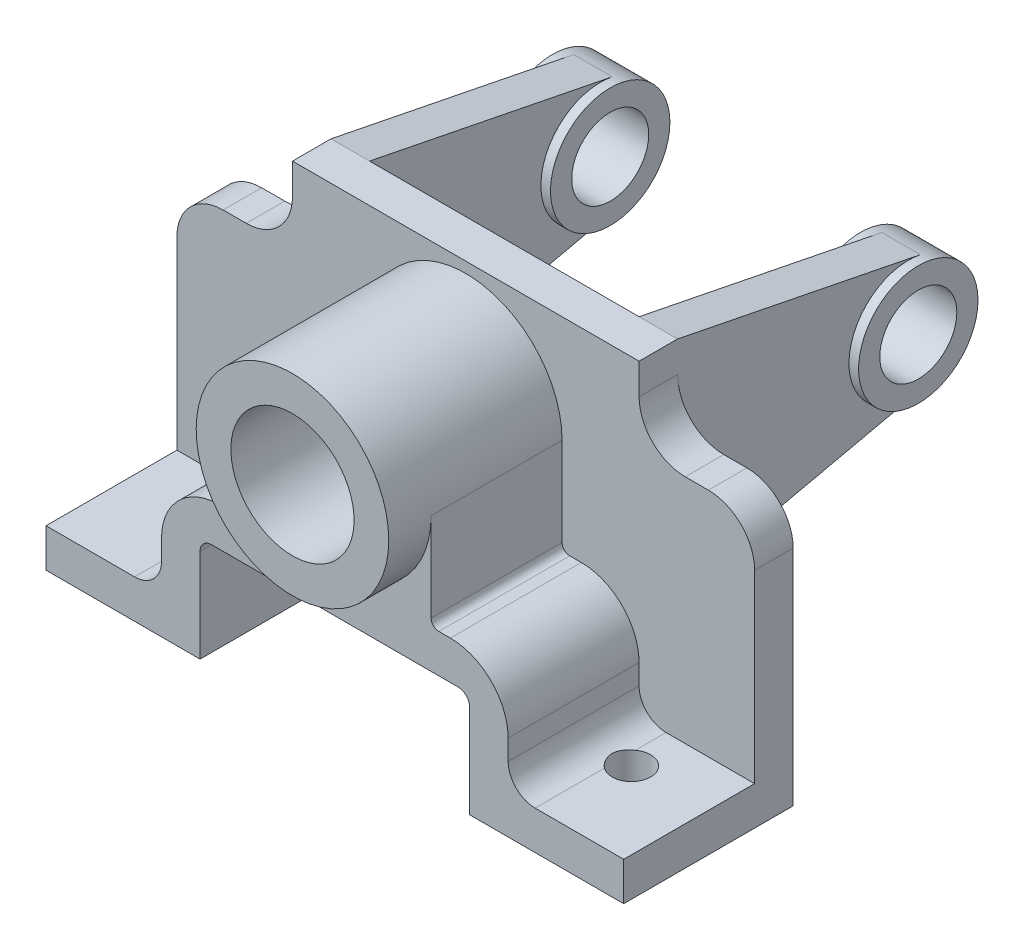
SolidWorks part; units mm, degrees
ref_plane "Front Plane" through (0, 0, 0) normal (0, 0, 1) x (1, 0, 0)
ref_plane "Top Plane" through (0, 0, 0) normal (0, 1, 0) x (1, 0, 0)
ref_plane "Right Plane" through (0, 0, 0) normal (1, 0, 0) x (0, 0, -1)
sketch "Sketch1" plane through (0, 0, 0) normal (0, 0, 1) x (1, 0, 0)
  line L0 (-32, 0) -> (32, 0)
  line L1 (35, -3) -> (35, -27.2359)
  line L2 (35, -27.2359) -> (75, -27.2359)
  line L3 (75, -27.2359) -> (75, 30.7641)
  line L4 (63, 42.7641) -> (57, 42.7641)
  line L5 (45, 54.7641) -> (45, 62.7641)
  line L6 (45, 62.7641) -> (-45, 62.7641)
  line L7 (-45, 62.7641) -> (-45, 54.7641)
  line L8 (-57, 42.7641) -> (-63, 42.7641)
  line L9 (-75, 30.7641) -> (-75, -27.2359)
  line L10 (-75, -27.2359) -> (-35, -27.2359)
  line L11 (-35, -27.2359) -> (-35, -3)
  line L12 (0, 62.7641) -> (0, 0) construction
  arc A0 (-63, 42.7641) -> (-75, 30.7641) centre (-63, 30.7641) ccw
  arc A1 (-45, 54.7641) -> (-57, 42.7641) centre (-57, 54.7641) cw
  arc A2 (75, 30.7641) -> (63, 42.7641) centre (63, 30.7641) ccw
  arc A3 (57, 42.7641) -> (45, 54.7641) centre (57, 54.7641) cw
  arc A4 (32, 0) -> (35, -3) centre (32, -3) cw
  arc A5 (-32, 0) -> (-35, -3) centre (-32, -3) ccw
  point P4 (0, 0)
  point P15 (0, 62.7641)
  point P22 (-45, 42.7641)
  point P25 (75, 42.7641)
  point P28 (45, 42.7641)
  point P31 (35, 0)
  dimension "D6" = 90
  dimension "D7" = 42.7641
  dimension "D8" = 12
  dimension "D9" = 3
  dimension "D1" = 70
  dimension "D2" = 150
  dimension "D3" = 40
  dimension "D4" = 20
  dimension "D5" = 70
extrude "Boss-Extrude2" add sketch "Sketch1" against normal blind 10
sketch "Sketch2" plane through (0, 0, 0) normal (0, 0, 1) x (1, 0, 0)
  line L0 (0, 0) -> (0, 35) construction
  circle A0 centre (0, 35) radius 25
  circle A1 centre (0, 35) radius 16
  dimension "D2" = 50
  dimension "D3" = 32
  dimension "D1" = 35
extrude "Boss-Extrude4" add sketch "Sketch2" along normal blind 45
sketch "Sketch3" plane through (0, 0, 0) normal (0, 0, 1) x (1, 0, 0)
  line L0 (-75, -17.2359) -> (-52, -17.2359)
  line L1 (-75, 30.7641) -> (-75, -27.2359) construction
  line L2 (-45, -10.2359) -> (-45, -5)
  line L3 (-30, 10) -> (-27, 10)
  line L4 (-25, 12) -> (-25, 35)
  line L5 (-75, -27.2359) -> (-35, -27.2359) construction
  line L6 (-35, -27.2359) -> (-35, -3) construction
  line L7 (-32, 0) -> (32, 0) construction
  line L8 (0, 0) -> (0, 35) construction
  line L9 (30, 10) -> (27, 10)
  line L10 (75, -17.2359) -> (52, -17.2359)
  line L11 (45, -10.2359) -> (45, -5)
  line L12 (25, 12) -> (25, 35)
  line L13 (-75, -17.2359) -> (-75, -27.2359)
  line L14 (-75, -27.2359) -> (-35, -27.2359)
  line L15 (-35, -27.2359) -> (-35, -3)
  line L17 (-32, 0) -> (32, 0)
  line L19 (35, -3) -> (35, -27.2359)
  line L20 (35, -27.2359) -> (75, -27.2359)
  line L21 (75, -27.2359) -> (75, -17.2359)
  circle A0 centre (0, 35) radius 25 construction
  arc A1 (-45, -5) -> (-30, 10) centre (-30, -5) cw
  arc A2 (-52, -17.2359) -> (-45, -10.2359) centre (-52, -10.2359) ccw
  arc A3 (-27, 10) -> (-25, 12) centre (-27, 12) ccw
  arc A4 (52, -17.2359) -> (45, -10.2359) centre (52, -10.2359) cw
  arc A5 (45, -5) -> (30, 10) centre (30, -5) ccw
  arc A6 (27, 10) -> (25, 12) centre (27, 12) cw
  arc A7 (-25, 35) -> (25, 35) centre (0, 35) ccw
  arc A8 (-35, -3) -> (-32, 0) centre (-32, -3) cw
  arc A9 (35, -3) -> (32, 0) centre (32, -3) ccw
  dimension "D4" = 15
  dimension "D5" = 7
  dimension "D6" = 2
  dimension "D1" = 10
  dimension "D2" = 10
  dimension "D3" = 10
extrude "Boss-Extrude5" add sketch "Sketch3" along normal blind 34
sketch "Sketch4" plane through (0, -27.2359, 0) normal (0, -1, 0) x (1, 0, 0)
  line L0 (0, 34) -> (0, -10) construction
  line L1 (-32, 34) -> (32, 34) construction
  line L2 (-32, -10) -> (32, -10) construction
  line L4 (-75, 34) -> (-35, 34) construction
  line L5 (35, 34) -> (75, 34) construction
  circle A0 centre (-55, 12) radius 5
  circle A1 centre (55, 12) radius 5
  dimension "D1" = 10
  dimension "D2" = 10
  dimension "D3" = 55
  dimension "D4" = 110
  dimension "D5" = 22
  dimension "D6" = 22
extrude "Cut-Extrude1" cut sketch "Sketch4" against normal blind 34
ref_plane "Plane1" through (40, 0, 0) normal (1, 0, 0) x (0, 0, -1)
sketch "Sketch6" plane through (40, 0, 0) normal (1, 0, 0) x (0, 0, -1)
  line L0 (-45, 35) -> (70, 35) construction
  line L1 (-45, 60) -> (-45, 10) construction
  line L2 (10, -27.2359) -> (10, 30.7641) construction
  circle A0 centre (70, 35) radius 15.5
  circle A1 centre (70, 35) radius 10
  dimension "D2" = 31
  dimension "D3" = 20
  dimension "D1" = 60
extrude "Boss-Extrude6" add sketch "Sketch6" along normal mid plane 15 separate body
sketch "Sketch7" plane through (40, 0, 0) normal (1, 0, 0) x (0, 0, -1)
  line L0 (10, 62.7641) -> (73.0299, 50.201)
  line L1 (10, 5.7136) -> (73.3795, 19.8729)
  line L2 (10, -27.2359) -> (10, 30.7641) construction
  line L3 (10, 62.7641) -> (10, 5.7136)
  circle A0 centre (70, 35) radius 15.5 construction
  arc A1 (73.3795, 19.8729) -> (73.0299, 50.201) centre (70, 35) cw
  dimension "D1" = 57.0505
extrude "Boss-Extrude8" add sketch "Sketch7" along normal mid plane 10 contours L0 A1 L1 L3
ref_plane "Plane2" through (-40, 0, 0) normal (1, 0, 0) x (0, 0, -1)
sketch "Sketch8" plane through (-40, 0, 0) normal (1, 0, 0) x (0, 0, -1)
  circle A0 centre (70, 35) radius 10
  circle A1 centre (70, 35) radius 15.5
  dimension "D1" = 31
  dimension "D2" = 20
extrude "Boss-Extrude9" add sketch "Sketch8" along normal mid plane 15 separate body
sketch "Sketch9" plane through (-40, 0, 0) normal (1, 0, 0) x (0, 0, -1)
  line L0 (73.0299, 50.201) -> (10, 62.7641)
  line L1 (10, 62.7641) -> (10, 5.7136)
  line L2 (10, 5.7136) -> (73.3795, 19.8729)
  circle A0 centre (70, 35) radius 15.5 construction
  arc A1 (73.0299, 50.201) -> (73.3795, 19.8729) centre (70, 35) ccw
extrude "Boss-Extrude10" add sketch "Sketch9" along normal mid plane 10 contours L0 L1 L2 A1
